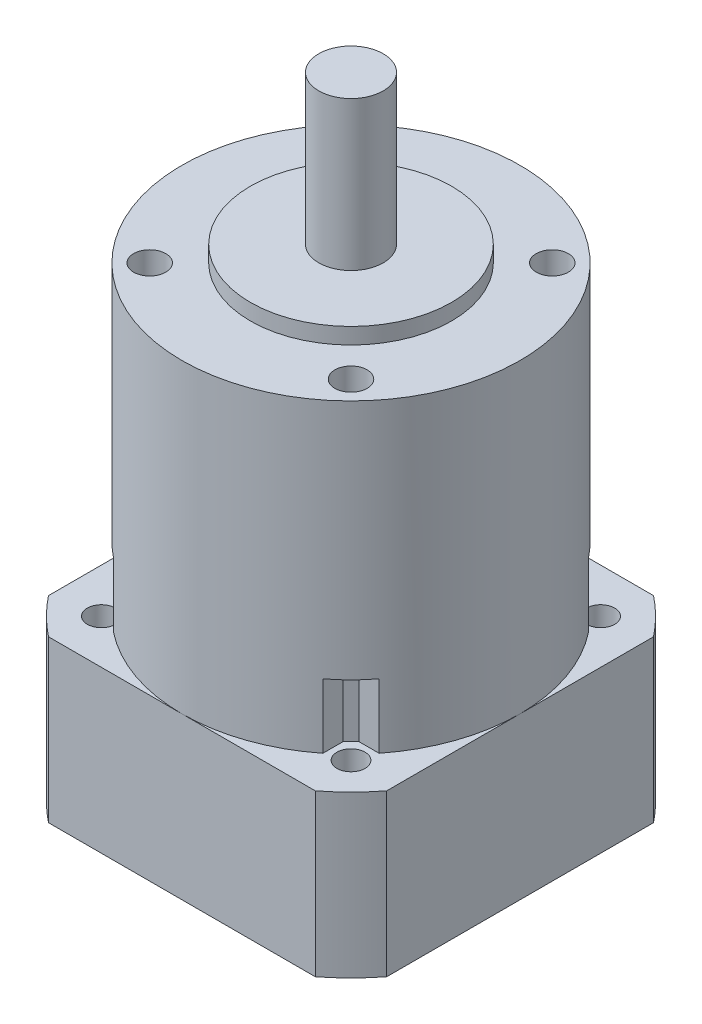
SolidWorks part; units mm, degrees
ref_plane "前视基准面" through (0, 0, 0) normal (0, 0, 1) x (1, 0, 0)
ref_plane "上视基准面" through (0, 0, 0) normal (0, 1, 0) x (1, 0, 0)
ref_plane "右视基准面" through (0, 0, 0) normal (1, 0, 0) x (0, 0, -1)
sketch "草图1" plane through (0, 0, 0) normal (0, 1, 0) x (1, 0, 0)
  line L1 (-21, 21) -> (21, 21)
  line L2 (-21, 21) -> (-21, -21)
  line L3 (-21, -21) -> (21, -21)
  line L4 (21, 21) -> (21, -21)
  line L5 (-21, 21) -> (21, -21) construction
  line L6 (-21, -21) -> (21, 21) construction
  circle A0 centre (0, 0) radius 26.75
  point P0 (0, 0)
  dimension "D3" = 53.5
  dimension "D1" = 42
  dimension "D2" = 42
extrude "凸台-拉伸1" add sketch "草图1" along normal blind 20 contours L3 A0 L4 L1 L2
sketch "草图2" plane through (0, 20, 0) normal (0, 1, 0) x (1, 0, 0)
  circle A0 centre (0, 0) radius 21
  dimension "D1" = 42
extrude "凸台-拉伸2" add sketch "草图2" along normal blind 38
sketch "草图3" plane through (0, 58, 0) normal (0, 1, 0) x (1, 0, 0)
  circle A0 centre (0, 0) radius 12.5
  dimension "D1" = 25
extrude "凸台-拉伸3" add sketch "草图3" along normal blind 2
sketch "草图4" plane through (0, 60, 0) normal (0, 1, 0) x (1, 0, 0)
  circle A0 centre (0, 0) radius 4
  dimension "D1" = 8
extrude "凸台-拉伸4" add sketch "草图4" along normal blind 18.5
sketch "草图5" plane through (0, 0, 0) normal (0, -1, 0) x (1, 0, 0)
  line L1 (-15.5, 15.5) -> (15.5, 15.5) construction
  line L2 (-15.5, 15.5) -> (-15.5, -15.5) construction
  line L3 (-15.5, -15.5) -> (15.5, -15.5) construction
  line L4 (15.5, 15.5) -> (15.5, -15.5) construction
  line L5 (-15.5, 15.5) -> (15.5, -15.5) construction
  line L6 (-15.5, -15.5) -> (15.5, 15.5) construction
  circle A0 centre (15.5, 15.5) radius 1.75
  circle A1 centre (15.5, -15.5) radius 1.75
  circle A2 centre (-15.5, -15.5) radius 1.75
  circle A3 centre (-15.5, 15.5) radius 1.75
  point P0 (0, 0)
  point P16 (0, 0)
  dimension "D3" = 3.5
  dimension "D1" = 31
  dimension "D2" = 31
  dimension "D4" = 4
extrude "切除-拉伸1" cut sketch "草图5" against normal blind 22.5
sketch "草图6" plane through (0, 20, 0) normal (0, 1, 0) x (1, 0, 0)
  line L0 (-13, -13) -> (-18, -13)
  line L1 (13, -13) -> (18, -13)
  line L2 (13, -13) -> (13, -18)
  line L3 (13, -18) -> (18, -18)
  line L4 (18, -13) -> (18, -18)
  line L5 (13, -13) -> (18, -18) construction
  line L6 (13, -18) -> (18, -13) construction
  line L7 (-13, -13) -> (-13, -18)
  line L8 (-13, -18) -> (-18, -18)
  line L9 (-18, -13) -> (-18, -18)
  line L10 (-13, 13) -> (-13, 18)
  line L11 (-13, 13) -> (-18, 13)
  line L12 (-18, 13) -> (-18, 18)
  line L13 (-13, 18) -> (-18, 18)
  line L14 (13, 13) -> (18, 13)
  line L15 (13, 13) -> (13, 18)
  line L16 (13, 18) -> (18, 18)
  line L17 (18, 13) -> (18, 18)
  point P0 (15.5, -15.5)
  point P21 (0, 0)
  dimension "D1" = 5
  dimension "D2" = 5
  dimension "D3" = 4
extrude "切除-拉伸2" cut sketch "草图6" along normal blind 8
chamfer "倒角1" distance 1 angle 45 4 edges at (13, 24, -13) (-13, 24, -13) (-13, 24, 13) (13, 24, 13)
sketch "草图7" plane through (0, 0, 0) normal (0, -1, 0) x (1, 0, 0)
  circle A0 centre (0, 0) radius 12
  dimension "D1" = 24
extrude "切除-拉伸3" cut sketch "草图7" against normal blind 23
sketch "草图8" plane through (0, 23, 0) normal (0, -1, 0) x (1, 0, 0)
  line L0 (-0.5, 2.5005) -> (-0.5, 10.9886)
  line L1 (0, 0) -> (0, 1.526) construction
  line L2 (0.5, 2.5005) -> (0.5, 10.9886)
  circle A0 centre (0, 0) radius 11
  circle A1 centre (0, 0) radius 2.55
  dimension "D1" = 22
  dimension "D2" = 5.1
  dimension "D3" = 1
extrude "凸台-拉伸5" add sketch "草图8" along normal blind 20 contours A1 L0 A0 L2
sketch "草图9" plane through (0, 58, 0) normal (0, 1, 0) x (1, 0, 0)
  line L1 (12.5, -12.5) -> (-12.5, -12.5) construction
  line L2 (12.5, -12.5) -> (12.5, 12.5) construction
  line L3 (12.5, 12.5) -> (-12.5, 12.5) construction
  line L4 (-12.5, -12.5) -> (-12.5, 12.5) construction
  line L5 (12.5, -12.5) -> (-12.5, 12.5) construction
  line L6 (12.5, 12.5) -> (-12.5, -12.5) construction
  circle A0 centre (12.5, 12.5) radius 2
  circle A1 centre (12.5, -12.5) radius 2
  circle A2 centre (-12.5, -12.5) radius 2
  circle A3 centre (-12.5, 12.5) radius 2
  point P2 (0, 0)
  point P17 (0, 0)
  dimension "D1" = 4
  dimension "D2" = 25
  dimension "D3" = 4
extrude "切除-拉伸4" cut sketch "草图9" against normal blind 13
